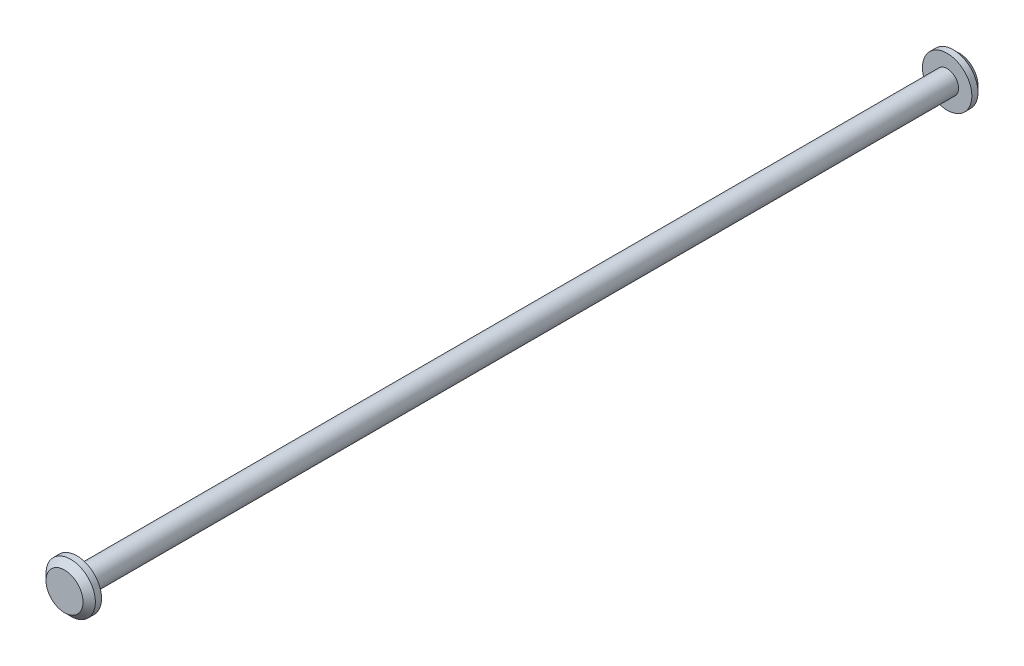
SolidWorks part; units mm, degrees
ref_plane "정면" through (0, 0, 0) normal (0, 0, 1) x (1, 0, 0)
ref_plane "윗면" through (0, 0, 0) normal (0, 1, 0) x (1, 0, 0)
ref_plane "우측면" through (0, 0, 0) normal (1, 0, 0) x (0, 0, -1)
sketch "스케치1" plane through (0, 0, 0) normal (0, 0, 1) x (1, 0, 0)
  circle A0 centre (0, 0) radius 0.925
  dimension "D1" = 1.85
extrude "보스-돌출1" add sketch "스케치1" along normal blind 70.5
sketch "스케치2" plane through (0, 0, 70.5) normal (0, 0, 1) x (1, 0, 0)
  circle A0 centre (0, 0) radius 2
  dimension "D1" = 4
extrude "보스-돌출2" add sketch "스케치2" along normal blind 1
sketch "스케치3" plane through (0, 0, 0) normal (0, 0, -1) x (-1, 0, 0)
  circle A0 centre (0, 0) radius 2
  dimension "D1" = 4
extrude "보스-돌출3" add sketch "스케치3" along normal blind 1
chamfer "모따기1" distance 0.5 angle 45 1 edges at (2, 0, 71.5)
chamfer "모따기2" distance 0.5 angle 45 1 edges at (-2, 0, -1)
